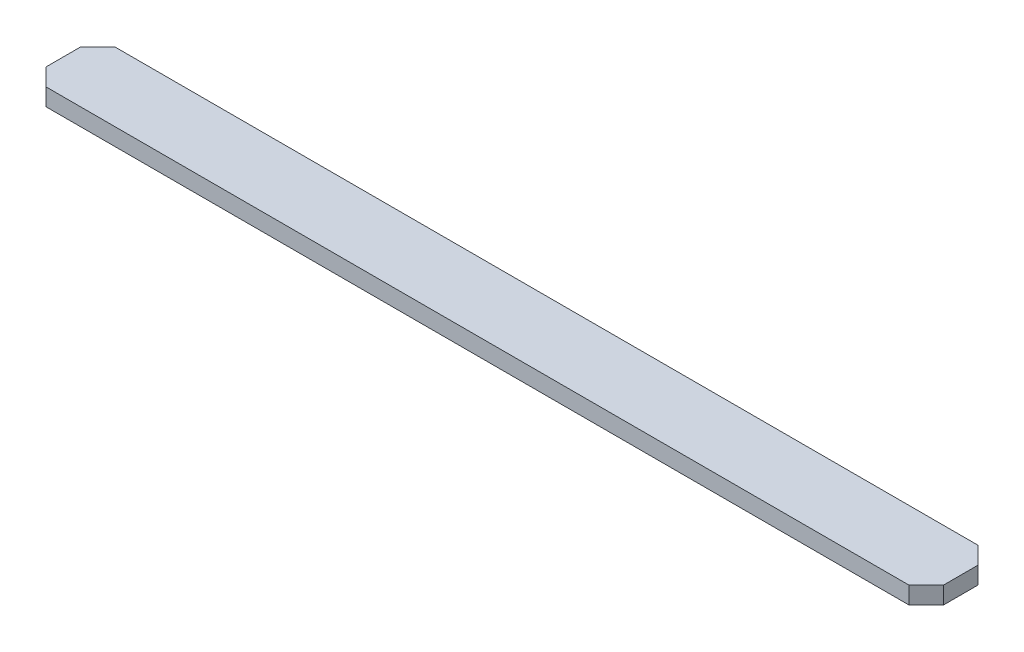
SolidWorks part; units mm, degrees
ref_plane "Front Plane" through (0, 0, 0) normal (0, 0, 1) x (1, 0, 0)
ref_plane "Top Plane" through (0, 0, 0) normal (0, 1, 0) x (1, 0, 0)
ref_plane "Right Plane" through (0, 0, 0) normal (1, 0, 0) x (0, 0, -1)
sketch "Sketch1" plane through (0, 0, 0) normal (0, 1, 0) x (1, 0, 0)
  line L1 (-26, 2) -> (26, 2)
  line L2 (-26, 2) -> (-26, -2)
  line L3 (-26, -2) -> (26, -2)
  line L4 (26, 2) -> (26, -2)
  line L5 (-26, 2) -> (26, -2) construction
  line L6 (-26, -2) -> (26, 2) construction
  point P0 (0, 0)
  dimension "D1" = 52
  dimension "D2" = 4
extrude "Boss-Extrude1" add sketch "Sketch1" along normal blind 1
chamfer "Chamfer1" distance 1 angle 45 4 edges at (-26, 0.5, -2) (-26, 0.5, 2) (26, 0.5, -2) (26, 0.5, 2)
